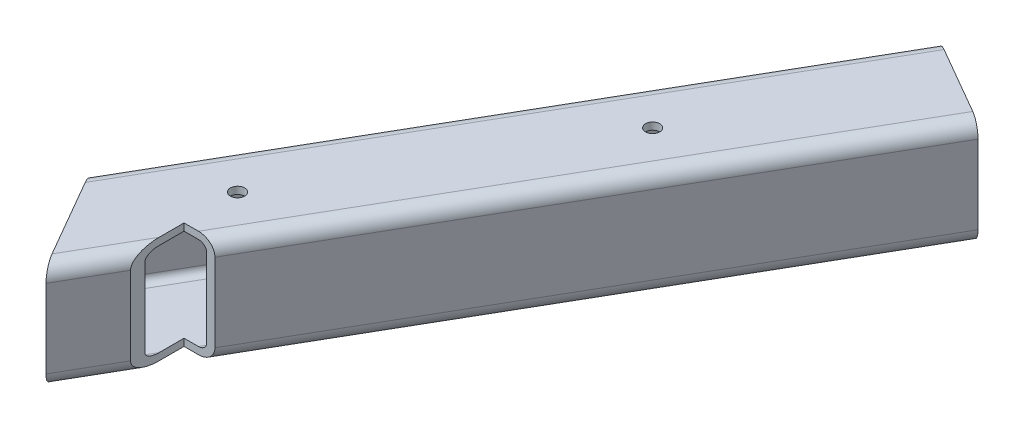
SolidWorks part; units mm, degrees
ref_plane "前视基准面" through (0, 0, 0) normal (0, 0, 1) x (1, 0, 0)
ref_plane "上视基准面" through (0, 0, 0) normal (0, 1, 0) x (1, 0, 0)
ref_plane "右视基准面" through (0, 0, 0) normal (1, 0, 0) x (0, 0, -1)
sketch "草图1" plane through (0, 0, 0) normal (0, 1, 0) x (1, 0, 0)
  line L1 (52, 0) -> (26, 45.0333)
  line L2 (26, 45.0333) -> (-26, 45.0333)
  line L3 (-26, 45.0333) -> (-52, 0)
  line L4 (-52, 0) -> (-26, -45.0333)
  line L5 (-26, -45.0333) -> (26, -45.0333)
  line L6 (26, -45.0333) -> (52, 0)
  circle A0 centre (0, 0) radius 45.0333 construction
  circle A1 centre (0, 0) radius 240
  dimension "D2" = 480
  dimension "D1" = 52
sketch "草图3" plane through (0, 0, 0) normal (0, 1, 0) x (1, 0, 0)
  line L0 (-52, 0) -> (38, 155.8846)
  line L1 (-26, 45.0333) -> (-52, 0) construction
  point P3 (-5.0493, 154.5965)
  dimension "D1" = 180
ref_plane "基准面1" through (-52, 0, 0) normal (0.5, 0, -0.866) x (-0.866, 0, -0.5)
sketch "草图5" plane through (-52, 0, 0) normal (0.5, 0, -0.866) x (-0.866, 0, -0.5)
  line L0 (-11, -13) -> (11, -13)
  line L1 (-11, -15) -> (11, -15)
  line L2 (-15, -11) -> (-15, 11)
  line L3 (-11, 15) -> (11, 15)
  line L4 (15, -11) -> (15, 11)
  line L5 (13, -11) -> (13, 11)
  line L6 (-11, 13) -> (11, 13)
  line L7 (-13, -11) -> (-13, 11)
  arc A0 (-11, -15) -> (-15, -11) centre (-11, -11) cw
  arc A1 (11, -15) -> (15, -11) centre (11, -11) ccw
  arc A2 (11, 15) -> (15, 11) centre (11, 11) cw
  arc A3 (-15, 11) -> (-11, 15) centre (-11, 11) cw
  arc A4 (11, -13) -> (13, -11) centre (11, -11) ccw
  arc A5 (11, 13) -> (13, 11) centre (11, 11) cw
  arc A6 (-13, 11) -> (-11, 13) centre (-11, 11) cw
  arc A7 (-11, -13) -> (-13, -11) centre (-11, -11) cw
  point P24 (-15, 0)
  point P26 (0, 15)
  dimension "D4" = 4
  dimension "D5" = 2
  dimension "D1" = 30
  dimension "D2" = 30
  dimension "D3" = 2
extrude "凸台-拉伸1" add sketch "草图5" along normal blind 200
sketch "草图7" plane through (0, 0, 0) normal (0, 1, 0) x (1, 0, 0)
  line L0 (-52, 0) -> (-26, -45.0333) construction
  line L1 (-52, 0) -> (-26, -45.0333) construction
  line L2 (2.8511, -65.0049) -> (-65.5279, 53.431)
  line L3 (-23.1297, -80.0049) -> (-91.5086, 38.431)
  line L4 (-65.5279, 53.431) -> (-91.5086, 38.431)
  line L5 (2.8511, -65.0049) -> (-23.1297, -80.0049)
  line L6 (60.9904, 165.7051) -> (-39.0096, -7.5) construction
  line L7 (60.9904, 165.7051) -> (-34.6795, 0) construction
  line L9 (-17.3397, -30.0333) -> (71.6167, -30.0333) construction
  line L10 (-26, -45.0333) -> (26, -45.0333) construction
  dimension "D1" = 15
  dimension "D2" = 15
extrude "切除-拉伸1" cut sketch "草图7" against normal through all both and the other way through all
sketch "草图8" plane through (0, 0, 0) normal (0, 1, 0) x (1, 0, 0)
  line L0 (48, 173.2051) -> (-43.3397, 15) construction
  line L1 (38.4737, 178.7051) -> (57.5263, 167.7051) construction
  line L2 (-36.9889, 4) -> (-49.6906, 26) construction
  circle A0 centre (-26, 45.0333) radius 2
  circle A2 centre (0, 0) radius 120 construction
  circle A3 centre (16.6147, 118.8442) radius 2
  dimension "D1" = 4
  dimension "D2" = 240
  dimension "D3" = 4
extrude "切除-拉伸2" cut sketch "草图8" against normal through all both and the other way through all
sketch "草图9" plane through (0, 0, 0) normal (0, 1, 0) x (1, 0, 0)
  line L0 (26, 30.0333) -> (-26, 30.0333)
  line L1 (-26, 30.0333) -> (-26, 5.0333)
  line L2 (-26, 5.0333) -> (26, 5.0333)
  line L3 (26, 5.0333) -> (26, 30.0333)
  line L4 (26, 45.0333) -> (-26, 45.0333) construction
  point P6 (0, 0)
  point P8 (0, 0)
  dimension "D1" = 15
  dimension "D2" = 25
extrude "切除-拉伸3" cut sketch "草图9" against normal through all both and the other way through all
